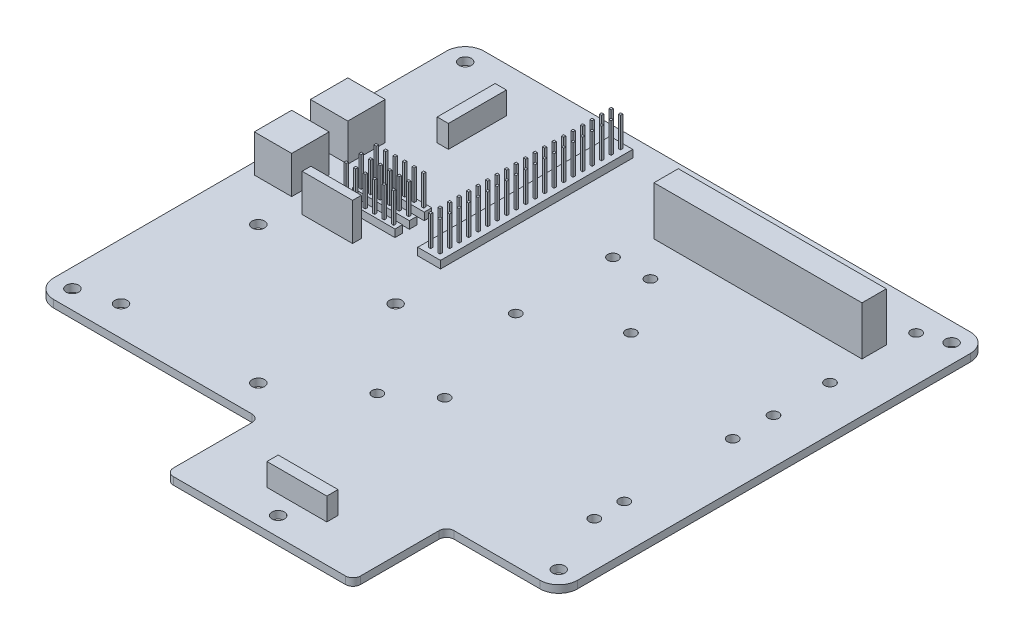
SolidWorks part; units mm, degrees
ref_plane "Front Plane" through (0, 0, 0) normal (0, 0, 1) x (1, 0, 0)
ref_plane "Top Plane" through (0, 0, 0) normal (0, 1, 0) x (1, 0, 0)
ref_plane "Right Plane" through (0, 0, 0) normal (1, 0, 0) x (0, 0, -1)
sketch "Sketch2" plane through (0, 0, 0) normal (0, 1, 0) x (1, 0, 0)
  line L7 (55, 50) -> (-85, 50)
  line L12 (-85, 50) -> (-85, -65)
  line L13 (-85, -65) -> (55, -65)
  line L16 (55, -65) -> (55, 50)
  point P0 (0, 0)
  dimension "D1" = 85
  dimension "D2" = 50
  dimension "D3" = 115
  dimension "D6" = 55
extrude "Boss-Extrude1" add sketch "Sketch2" along normal blind 2
sketch "Sketch7" plane through (0, 2, 0) normal (0, 1, 0) x (1, 0, 0)
  line L0 (-15, 19.5) -> (43, 19.5) construction
  line L1 (43, -6.5) -> (-15, -6.5) construction
  line L2 (43, -6.5) -> (43, 42.5) construction
  line L3 (43, 42.5) -> (-15, 42.5) construction
  line L4 (-15, -6.5) -> (-15, 42.5) construction
  line L5 (43, -6.5) -> (-15, 42.5) construction
  line L6 (43, 42.5) -> (-15, -6.5) construction
  line L7 (39, 40) -> (-11, 40) construction
  line L8 (39, 40) -> (39, 45) construction
  line L9 (39, 45) -> (-11, 45) construction
  line L10 (-11, 40) -> (-11, 45) construction
  line L11 (39, 40) -> (-11, 45) construction
  line L12 (39, 45) -> (-11, 40) construction
  line L14 (43, -43.5) -> (-15, -43.5) construction
  line L15 (43, -43.5) -> (43, 42.5) construction
  line L16 (43, 42.5) -> (-15, 42.5) construction
  line L17 (-15, -43.5) -> (-15, 42.5) construction
  line L18 (43, -43.5) -> (-15, 42.5) construction
  line L19 (43, 42.5) -> (-15, -43.5) construction
  line L20 (39, 50) -> (-11, 50) construction
  line L21 (39, 50) -> (39, 55) construction
  line L22 (39, 55) -> (-11, 55) construction
  line L23 (-11, 50) -> (-11, 55) construction
  line L24 (39, 50) -> (-11, 55) construction
  line L25 (39, 55) -> (-11, 50) construction
  line L28 (55, 50) -> (-85, 50) construction
  circle A0 centre (-15, 42.5) radius 1.4
  circle A1 centre (43, 42.5) radius 1.4
  circle A2 centre (-15, -6.5) radius 1.4
  circle A3 centre (43, -6.5) radius 1.4
  circle A4 centre (-15, 19.5) radius 1.4
  circle A5 centre (43, 19.5) radius 1.4
  circle A8 centre (-15, -43.5) radius 1.4
  circle A9 centre (43, -43.5) radius 1.4
  point P0 (14, 18)
  point P9 (14, 42.5)
  point P18 (14, 52.5)
  point P19 (14, -0.5)
  dimension "D3" = 2.8
  dimension "D1" = 49
  dimension "D2" = 58
  dimension "D4" = 23
  dimension "D5" = 86
  dimension "D6" = 5
  dimension "D7" = 14
  dimension "D8" = 5
  dimension "D10" = 50
  dimension "D11" = 5
extrude "Cut-Extrude1" cut sketch "Sketch7" against normal blind 10
sketch "Sketch9" plane through (0, 2, 0) normal (0, 1, 0) x (1, 0, 0)
  line L0 (-85, -65) -> (55, -65) construction
  line L1 (-25, -65) -> (25, -65)
  line L2 (-25, -65) -> (-25, -90)
  line L3 (-25, -90) -> (25, -90)
  line L4 (25, -65) -> (25, -90)
  line L5 (25, -65) -> (55, -65) construction
  line L6 (-85, -65) -> (-25, -65) construction
  line L7 (0, 0) -> (0, -65) construction
  dimension "D1" = 25
  dimension "D2" = 50
extrude "Boss-Extrude2" add sketch "Sketch9" against normal up to surface (2 mm away) up to face at (-15, 0, -18.1)
sketch "Sketch11" plane through (0, 2, 0) normal (0, 1, 0) x (1, 0, 0)
  line L0 (43, -43.5) -> (-15, 42.5) construction
  line L1 (4.9, 4.4) -> (43, 4.4) construction
  line L2 (4.9, 4.4) -> (4.9, 42.5) construction
  line L3 (4.9, 42.5) -> (43, 42.5) construction
  line L4 (43, 4.4) -> (43, 42.5) construction
  line L5 (4.9, 4.4) -> (43, 42.5) construction
  line L6 (4.9, 42.5) -> (43, 4.4) construction
  line L7 (-5, -35.5) -> (43, -35.5) construction
  line L8 (-5, -35.5) -> (-5, 19.5) construction
  line L9 (-5, 19.5) -> (43, 19.5) construction
  line L10 (43, -35.5) -> (43, 19.5) construction
  line L11 (-5, -35.5) -> (43, 19.5) construction
  line L12 (-5, 19.5) -> (43, -35.5) construction
  circle A0 centre (-5, 19.5) radius 1.4
  circle A1 centre (4.9, 42.5) radius 1.4
  circle A2 centre (4.9, 4.4) radius 1.4
  circle A3 centre (-5, -35.5) radius 1.4
  circle A4 centre (43, -35.5) radius 1.4
  circle A5 centre (-15, 42.5) radius 1.4 construction
  circle A6 centre (43, 4.4) radius 1.4
  point P0 (23.95, 23.45)
  point P5 (19.0328, -7.9624)
  dimension "D1" = 55
  dimension "D2" = 48
  dimension "D3" = 38.1
extrude "Cut-Extrude2" cut sketch "Sketch11" against normal through all
sketch "Sketch12" plane through (0, 2, 0) normal (0, 1, 0) x (1, 0, 0)
  line L0 (-15, 42.5) -> (43, 42.5) construction
  line L7 (-13.8, 35.75) -> (41.8, 35.75)
  line L8 (-13.8, 35.75) -> (-13.8, 29.25)
  line L9 (-13.8, 29.25) -> (41.8, 29.25)
  line L10 (41.8, 35.75) -> (41.8, 29.25)
  line L11 (-13.8, 35.75) -> (41.8, 29.25) construction
  line L12 (-13.8, 29.25) -> (41.8, 35.75) construction
  line L13 (14, 42.5) -> (14, 32.5) construction
  point P5 (14, 32.5)
  dimension "D1" = 55.6
  dimension "D2" = 6.5
  dimension "D3" = 10
extrude "Boss-Extrude3" add sketch "Sketch12" along normal blind 13
sketch "Sketch16" plane through (0, 0, 0) normal (0, -1, 0) x (1, 0, 0)
  line L0 (0, 0) -> (0, -10) construction
  line L1 (0, -10) -> (-29, -10) construction
  line L2 (0, -10) -> (29, -10) construction
  circle A0 centre (-29, -10) radius 3
  circle A1 centre (29, -10) radius 3
  dimension "D3" = 6
  dimension "D1" = 29
  dimension "D2" = 10
extrude "Cut-Extrude4" [suppressed] cut sketch "Sketch16" against normal through all
sketch "Sketch17" plane through (0, 2, 0) normal (0, 1, 0) x (1, 0, 0)
  line L0 (55, 50) -> (-85, 50) construction
  line L1 (-40, 43.4) -> (-39.4, 43.4)
  line L2 (-40, 43.4) -> (-40, 44)
  line L3 (-40, 44) -> (-39.4, 44)
  line L4 (-39.4, 43.4) -> (-39.4, 44)
  line L5 (-40, 43.4) -> (-39.4, 44) construction
  line L6 (-40, 44) -> (-39.4, 43.4) construction
  point P0 (-39.7, 43.7)
  dimension "D1" = 0.6
  dimension "D2" = 40
  dimension "D3" = 6
extrude "Boss-Extrude7" add sketch "Sketch17" along normal blind 10
pattern_linear "LPattern1" count 20 spacing 2.54 along (0, 0, 1) count 2 spacing 2.54 along (1, 0, 0) of "Boss-Extrude7"
sketch "Sketch20" plane through (0, 2, 0) normal (0, 1, 0) x (1, 0, 0)
  line L0 (-85, -65) -> (-25, -65) construction
  line L1 (-33.3, -57) -> (-70, -57) construction
  line L2 (-33.3, -57) -> (-33.3, -20.3) construction
  line L3 (-33.3, -20.3) -> (-70, -20.3) construction
  line L4 (-70, -57) -> (-70, -20.3) construction
  line L5 (-33.3, -57) -> (-70, -20.3) construction
  line L6 (-33.3, -20.3) -> (-70, -57) construction
  line L8 (-85, 50) -> (-85, -65) construction
  circle A0 centre (-70, -20.3) radius 1.65
  circle A1 centre (-33.3, -20.3) radius 1.65
  circle A2 centre (-70, -57) radius 1.65
  circle A3 centre (-33.3, -57) radius 1.65
  point P0 (-51.65, -38.65)
  dimension "D2" = 3.3
  dimension "D1" = 36.7
  dimension "D3" = 8
  dimension "D4" = 15
extrude "Cut-Extrude5" cut sketch "Sketch20" against normal through all
sketch "Sketch21" plane through (0, 2, 0) normal (0, 1, 0) x (1, 0, 0)
  line L1 (-66.4814, -9.7712) -> (-53.0024, -9.7712)
  line L2 (-66.4814, -9.7712) -> (-66.4814, -12.1153)
  line L3 (-66.4814, -12.1153) -> (-53.0024, -12.1153)
  line L4 (-53.0024, -9.7712) -> (-53.0024, -12.1153)
  line L5 (-66.4814, -9.7712) -> (-53.0024, -12.1153) construction
  line L6 (-66.4814, -12.1153) -> (-53.0024, -9.7712) construction
  point P0 (-59.7419, -10.9433)
extrude "Boss-Extrude9" add sketch "Sketch21" along normal blind 10
sketch "Sketch22" plane through (0, 2, 0) normal (0, 1, 0) x (1, 0, 0)
  line L1 (-41.4407, 45.1346) -> (-35.3552, 45.1346)
  line L2 (-41.4407, 45.1346) -> (-41.4407, -6.2531)
  line L3 (-41.4407, -6.2531) -> (-35.3552, -6.2531)
  line L4 (-35.3552, 45.1346) -> (-35.3552, -6.2531)
extrude "Boss-Extrude10" add sketch "Sketch22" along normal blind 2
sketch "Sketch23" plane through (0, 2, 0) normal (0, 1, 0) x (1, 0, 0)
  line L0 (0, -90) -> (0, -85) construction
  line L1 (-80, 45) -> (50, 45) construction
  line L2 (-80, 45) -> (-80, -60) construction
  line L3 (-80, -60) -> (50, -60) construction
  line L4 (50, 45) -> (50, -60) construction
  line L5 (-25, -90) -> (25, -90) construction
  line L6 (-85, 50) -> (-85, -65) construction
  line L8 (55, 50) -> (-85, 50) construction
  line L9 (25, -65) -> (55, -65) construction
  line L10 (55, -65) -> (55, 50) construction
  circle A0 centre (-80, 45) radius 1.65
  circle A1 centre (50, 45) radius 1.65
  circle A2 centre (50, -60) radius 1.65
  circle A3 centre (-80, -60) radius 1.65
  circle A4 centre (0, -85) radius 1.65
  dimension "D3" = 3.3
  dimension "D1" = 5
  dimension "D2" = 5
  dimension "D4" = 5
  dimension "D5" = 5
  dimension "D6" = 5
extrude "Cut-Extrude6" cut sketch "Sketch23" against normal blind 2
fillet "Fillet1" radius 5 4 edges at (55, 1, -50) (55, 1, 65) (-85, 1, 65) (-85, 1, -50)
fillet "Fillet2" radius 2 4 edges at (25, 1, 65) (25, 1, 90) (-25, 1, 90) (-25, 1, 65)
sketch "Sketch24" plane through (0, 2, 0) normal (0, 1, 0) x (1, 0, 0)
  line L0 (-105.8881, -0.8833) -> (-105.8881, 10.6167) construction
  line L1 (-82, 15.6167) -> (-72, 15.6167)
  line L2 (-82, 15.6167) -> (-82, 5.6167)
  line L3 (-82, 5.6167) -> (-72, 5.6167)
  line L4 (-72, 15.6167) -> (-72, 5.6167)
  line L5 (-105.8881, 10.6167) -> (-82, 10.6167) construction
  line L6 (-85, 45) -> (-85, -60) construction
  dimension "D1" = 11.5
  dimension "D2" = 10
  dimension "D3" = 3
extrude "Boss-Extrude11" add sketch "Sketch24" along normal blind 10
sketch "Sketch25" plane through (0, 2, 0) normal (0, 1, 0) x (1, 0, 0)
  line L0 (-85, 45) -> (-85, -60) construction
  line L1 (-65, 38) -> (-62, 38)
  line L2 (-65, 38) -> (-65, 22.5)
  line L3 (-65, 22.5) -> (-62, 22.5)
  line L4 (-62, 38) -> (-62, 22.5)
  line L5 (-8, -77) -> (8, -77)
  line L6 (-8, -77) -> (-8, -80)
  line L7 (-8, -80) -> (8, -80)
  line L8 (8, -77) -> (8, -80)
  line L9 (50, 50) -> (-80, 50) construction
  line L10 (0, -80) -> (0, -90) construction
  line L11 (-23, -90) -> (23, -90) construction
  dimension "D1" = 15.5
  dimension "D2" = 3
  dimension "D3" = 20
  dimension "D4" = 12
  dimension "D5" = 16
  dimension "D6" = 3
  dimension "D7" = 10
extrude "Boss-Extrude12" add sketch "Sketch25" along normal blind 6
sketch "Sketch26" plane through (0, 2, 0) normal (0, 1, 0) x (1, 0, 0)
  line L0 (-39.4, 44) -> (-40, 44) construction
  line L1 (-63.0081, 4.1968) -> (-62.4081, 4.1968)
  line L2 (-63.0081, 4.1968) -> (-63.0081, 3.5968)
  line L3 (-63.0081, 3.5968) -> (-62.4081, 3.5968)
  line L4 (-62.4081, 4.1968) -> (-62.4081, 3.5968)
extrude "Boss-Extrude13" add sketch "Sketch26" along normal blind 10
pattern_linear "LPattern2" count 6 spacing 2.54 along (1, 0, 0) count 3 spacing 4 along (0, 0, 1) of "Boss-Extrude13"
sketch "Sketch27" plane through (0, 2, 0) normal (0, 1, 0) x (1, 0, 0)
  line L1 (-63.952, 4.7548) -> (-48.7061, 4.7548)
  line L2 (-63.952, 4.7548) -> (-63.952, 2.7548)
  line L3 (-63.952, 2.7548) -> (-48.7061, 2.7548)
  line L4 (-48.7061, 4.7548) -> (-48.7061, 2.7548)
  line L5 (-63.952, 0.7741) -> (-48.7061, 0.7741)
  line L6 (-63.952, 0.7741) -> (-63.952, -1.2259)
  line L7 (-63.952, -1.2259) -> (-48.7061, -1.2259)
  line L8 (-48.7061, 0.7741) -> (-48.7061, -1.2259)
  line L9 (-63.952, -3.0754) -> (-48.7061, -3.0754)
  line L10 (-63.952, -3.0754) -> (-63.952, -5.0754)
  line L11 (-63.952, -5.0754) -> (-48.7061, -5.0754)
  line L12 (-48.7061, -3.0754) -> (-48.7061, -5.0754)
  dimension "D1" = 2
extrude "Boss-Extrude14" add sketch "Sketch27" along normal blind 2
pattern_linear "LPattern3" count 2 spacing 15 along (0, 0, 1) of "Boss-Extrude11"
